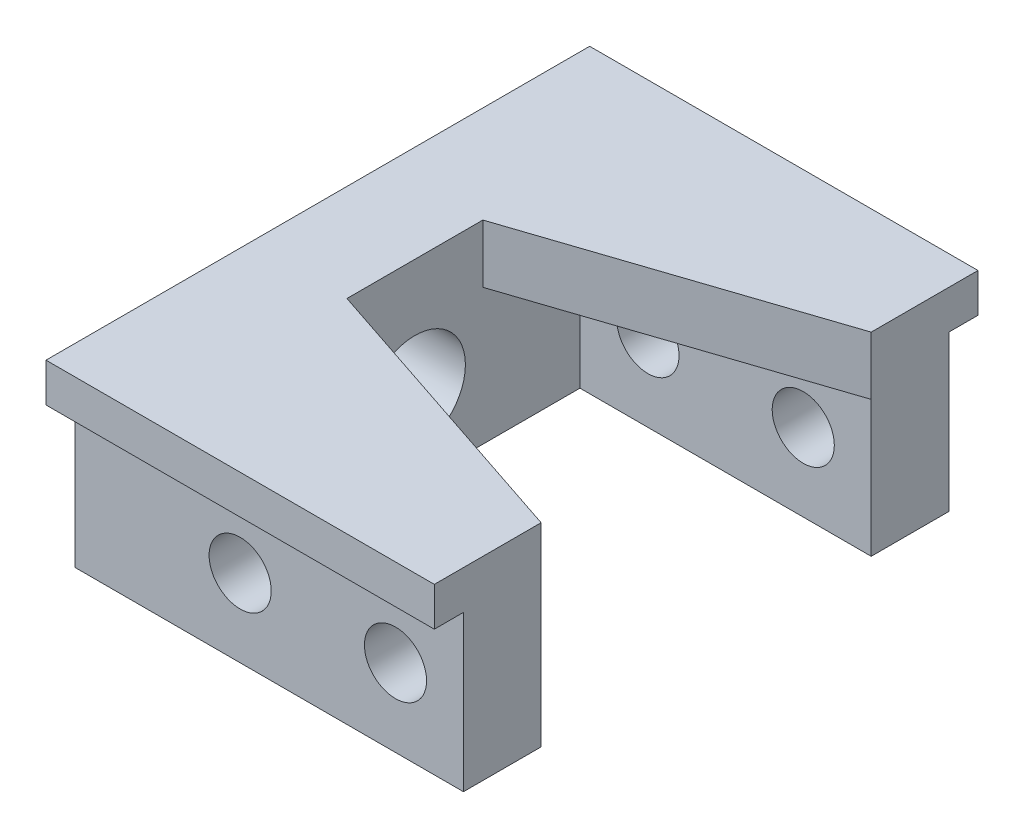
SolidWorks part; units mm, degrees
material "POM 乙缩醛共聚物"
ref_plane "前视基准面" through (0, 0, 0) normal (0, 0, 1) x (1, 0, 0)
ref_plane "上视基准面" through (0, 0, 0) normal (0, 1, 0) x (1, 0, 0)
ref_plane "右视基准面" through (0, 0, 0) normal (1, 0, 0) x (0, 0, -1)
sketch "草图1" plane through (0, 0, 0) normal (1, 0, 0) x (0, 0, -1)
  line L0 (0, 0) -> (0, 1.5) construction
  line L1 (12.5, -5.5) -> (-12.5, -5.5)
  line L2 (12.5, -5.5) -> (12.5, 5.5)
  line L3 (12.5, 5.5) -> (-12.5, 5.5)
  line L4 (-12.5, -5.5) -> (-12.5, 5.5)
  line L5 (12.5, -5.5) -> (-12.5, 5.5) construction
  line L6 (12.5, 5.5) -> (-12.5, -5.5) construction
  circle A0 centre (0, 1.5) radius 2.6
  point P0 (0, 0)
  dimension "D1" = 5.2
  dimension "D2" = 11
  dimension "D3" = 25
  dimension "D4" = 1.5
extrude "凸台-拉伸1" add sketch "草图1" along normal blind 5
sketch "草图2" plane through (5, 0, 0) normal (1, 0, 0) x (0, 0, -1)
  line L0 (0, 0) -> (0, 6.4242) construction
  line L1 (-8.5, -5.5) -> (-12.5, -5.5)
  line L2 (-8.5, -5.5) -> (-8.5, 5.5)
  line L3 (-8.5, 5.5) -> (-12.5, 5.5)
  line L4 (-12.5, -5.5) -> (-12.5, 5.5)
  line L5 (-8.5, -5.5) -> (-12.5, 5.5) construction
  line L6 (-8.5, 5.5) -> (-12.5, -5.5) construction
  line L7 (8.5, 5.5) -> (12.5, 5.5)
  line L8 (12.5, -5.5) -> (12.5, 5.5)
  line L9 (8.5, -5.5) -> (12.5, -5.5)
  line L10 (8.5, -5.5) -> (8.5, 5.5)
  point P0 (-10.5, 0)
  dimension "D1" = 4
extrude "凸台-拉伸2" add sketch "草图2" along normal blind 15
sketch "草图4" plane through (0, 0, 12.5) normal (0, 0, 1) x (1, 0, 0)
  line L0 (20, 1.5) -> (0, 1.5) construction
  line L1 (20, 5.5) -> (20, -5.5) construction
  line L2 (0, 5.5) -> (0, -5.5) construction
  line L3 (20, 5.5) -> (0, 5.5) construction
  circle A0 centre (16.5, 1.5) radius 1.6
  circle A1 centre (8.5, 1.5) radius 1.6
  dimension "D4" = 3.2
  dimension "D1" = 4
  dimension "D2" = 8.5
  dimension "D3" = 8
extrude "切除-拉伸1" cut sketch "草图4" against normal through all
sketch "草图7" plane through (0, 5.5, 0) normal (0, 1, 0) x (1, 0, 0)
  line L0 (20, 8.5) -> (5, 8.5)
  line L1 (0, 12.5) -> (0, -12.5) construction
  line L2 (0, 8.5) -> (0, 14)
  line L3 (0, 14) -> (20, 14)
  line L4 (20, 14) -> (20, 8.5)
  line L5 (20, 12.5) -> (0, 12.5) construction
  line L6 (0, 0) -> (9.0816, 0) construction
  line L7 (0, -14) -> (20, -14)
  line L8 (0, -8.5) -> (0, -14)
  line L9 (20, -8.5) -> (5, -8.5)
  line L10 (20, -14) -> (20, -8.5)
  line L11 (5, 8.5) -> (5, -8.5)
  line L12 (0, 8.5) -> (0, -8.5)
  dimension "D1" = 1.5
extrude "凸台-拉伸4" add sketch "草图7" along normal blind 2
sketch "草图6" plane through (0, 7.5, 0) normal (0, -1, 0) x (1, 0, 0)
  line L0 (20, 8.5) -> (5, 8.5)
  line L1 (5, 8.5) -> (5, 3.5)
  line L2 (5, 8.5) -> (5, -8.5) construction
  line L3 (5, 3.5) -> (20, 8.5)
  line L4 (0, 0) -> (11.2684, 0) construction
  line L5 (0, 12.5) -> (0, -12.5) construction
  line L6 (5, -8.5) -> (5, -3.5)
  line L7 (20, -8.5) -> (5, -8.5)
  line L8 (5, -3.5) -> (20, -8.5)
  dimension "D1" = 7
extrude "凸台-拉伸3" add sketch "草图6" along normal blind 3
sketch "草图8" plane through (0, -5.5, 0) normal (0, -1, 0) x (1, 0, 0)
  line L0 (20, -12.5) -> (0, -12.5) construction
  line L1 (0, -12.5) -> (20, -12.5)
  line L2 (0, -12.5) -> (0, 12.5)
  line L3 (0, 12.5) -> (20, 12.5)
  line L4 (20, -12.5) -> (20, 12.5)
  line L5 (0, -12.5) -> (20, 12.5) construction
  line L6 (0, 12.5) -> (20, -12.5) construction
  point P0 (10, 0)
extrude "切除-拉伸2" cut sketch "草图8" against normal blind 3
